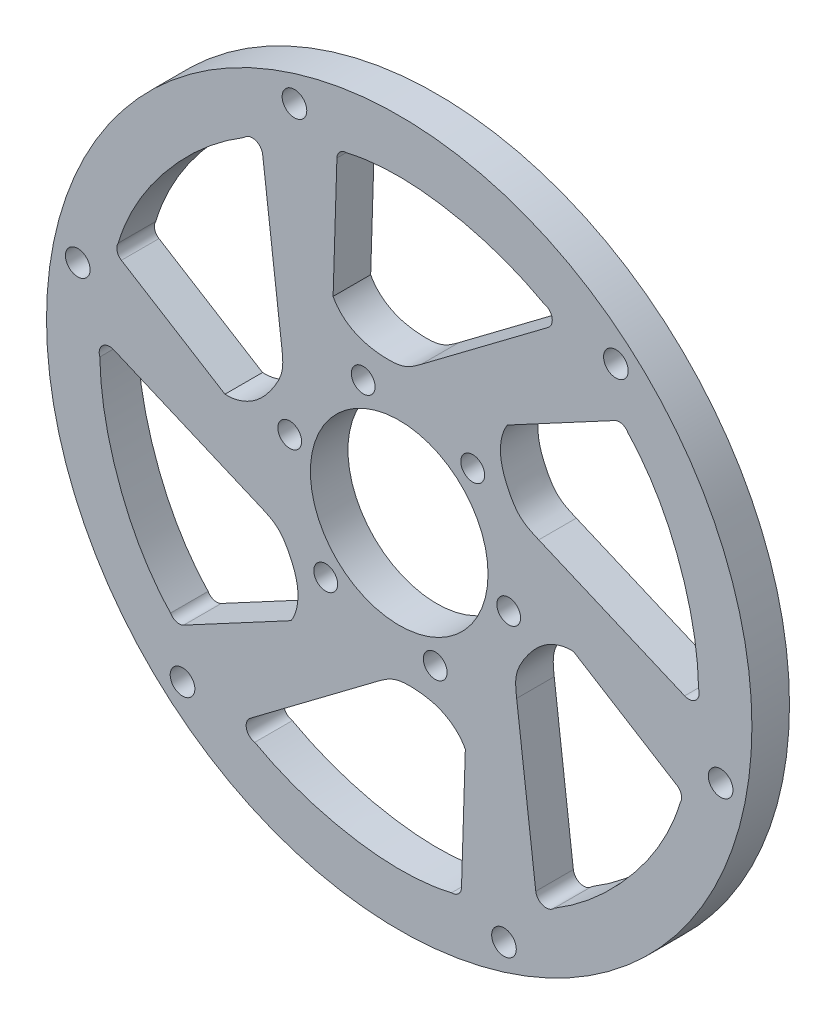
SolidWorks part; units mm, degrees
ref_plane "Piano frontale" through (0, 0, 0) normal (0, 0, 1) x (1, 0, 0)
ref_plane "Piano superiore" through (0, 0, 0) normal (0, 1, 0) x (1, 0, 0)
ref_plane "Piano destro" through (0, 0, 0) normal (1, 0, 0) x (0, 0, -1)
sketch "Schizzo1" plane through (0, 0, 0) normal (0, 0, 1) x (1, 0, 0)
  line L0 (32.5373, 57.7523) -> (32.9478, 70.8459)
  line L1 (42.0185, 56.1733) -> (55.6512, 66.4168)
  line L2 (54.6451, 46.1421) -> (70.3327, 39.4576)
  line L3 (51.2721, 55.1426) -> (62.8167, 61.3339)
  line L4 (52.2712, 30.1915) -> (54.326, 13.2635)
  line L5 (58.3793, 37.6129) -> (69.5134, 30.7107)
  line L6 (37.2706, 24.2722) -> (23.6379, 14.0286)
  line L7 (46.7518, 22.6931) -> (46.3413, 9.5995)
  line L8 (24.644, 34.3033) -> (8.9565, 40.9878)
  line L9 (28.0171, 25.3028) -> (16.4725, 19.1115)
  line L10 (27.018, 50.2539) -> (24.9631, 67.1819)
  line L11 (20.9098, 42.8325) -> (9.7757, 49.7347)
  circle A0 centre (39.6446, 40.2227) radius 37.92
  circle A1 centre (39.6446, 40.2227) radius 35.25 construction
  circle A2 centre (28.3817, 73.625) radius 1.325
  arc A3 (32.9478, 70.8459) -> (34.0242, 71.8569) centre (33.9915, 70.8132) cw
  arc A4 (55.6512, 66.4168) -> (55.1805, 68.4226) centre (54.9753, 67.3163) ccw
  circle A5 centre (39.6446, 40.2227) radius 9.55
  circle A6 centre (39.6446, 40.2227) radius 12 construction
  circle A7 centre (35.7744, 51.5815) radius 1.28
  circle A8 centre (47.5464, 49.2538) radius 1.28
  arc A9 (70.3327, 39.4576) -> (71.8343, 40.8681) centre (70.7737, 40.4927) ccw
  arc A10 (62.8167, 61.3339) -> (64.2304, 60.9072) centre (63.3102, 60.4137) cw
  circle A11 centre (62.9404, 66.6777) radius 1.325
  circle A12 centre (51.4166, 37.895) radius 1.28
  arc A13 (54.326, 13.2635) -> (56.2984, 12.6682) centre (55.4429, 13.3991) ccw
  arc A14 (69.5134, 30.7107) -> (69.8508, 29.273) centre (68.9633, 29.8232) cw
  circle A15 centre (74.2032, 33.2755) radius 1.325
  circle A16 centre (43.5148, 28.8639) radius 1.28
  arc A17 (23.6379, 14.0286) -> (24.1086, 12.0229) centre (24.3138, 13.1291) ccw
  arc A18 (46.3413, 9.5995) -> (45.2649, 8.5885) centre (45.2976, 9.6322) cw
  circle A19 centre (50.9074, 6.8204) radius 1.325
  circle A20 centre (31.7427, 31.1916) radius 1.28
  arc A21 (8.9565, 40.9878) -> (7.4548, 39.5773) centre (8.5154, 39.9527) ccw
  arc A22 (16.4725, 19.1115) -> (15.0587, 19.5382) centre (15.9789, 20.0318) cw
  circle A23 centre (16.3488, 13.7677) radius 1.325
  circle A24 centre (27.8725, 42.5504) radius 1.28
  arc A25 (24.9631, 67.1819) -> (22.9908, 67.7772) centre (23.8462, 67.0464) ccw
  arc A26 (9.7757, 49.7347) -> (9.4384, 51.1724) centre (10.3259, 50.6223) cw
  circle A27 centre (5.0859, 47.17) radius 1.325
  spline S0 degree 3 poles (32.5373, 57.7523) (33.0858, 56.6797) (34.8292, 55.2892) (37.667, 54.792) (40.192, 54.8224) (41.3967, 55.706) (42.0185, 56.1733) knots 0 0 0 0 0.33293 0.577053 0.800008 1 1 1 1
  spline S1 degree 3 poles (34.0242, 71.8569) (37.8131, 72.7545) (45.2372, 72.4651) (52.1771, 70.0854) (55.1805, 68.4226) knots 0 0 0 0 0.531114 1 1 1 1
  spline S2 degree 3 poles (51.2721, 55.1426) (50.6173, 54.1313) (50.2848, 51.9261) (51.2731, 49.22) (52.562, 47.0484) (53.9296, 46.447) (54.6451, 46.1421) knots 0 0 0 0 0.33293 0.577053 0.800008 1 1 1 1
  spline S3 degree 3 poles (64.2304, 60.9072) (66.9022, 58.0747) (70.3636, 51.5005) (71.7727, 44.3005) (71.8343, 40.8681) knots 0 0 0 0 0.531114 1 1 1 1
  spline S4 degree 3 poles (58.3793, 37.6129) (57.1761, 37.6743) (55.1002, 36.8597) (53.2507, 34.6507) (52.0145, 32.4487) (52.1774, 30.9637) (52.2712, 30.1915) knots 0 0 0 0 0.33293 0.577053 0.800008 1 1 1 1
  spline S5 degree 3 poles (69.8508, 29.273) (68.7336, 25.5429) (64.7709, 19.2581) (59.2401, 14.4378) (56.2984, 12.6682) knots 0 0 0 0 0.531114 1 1 1 1
  spline S6 degree 3 poles (46.7518, 22.6931) (46.2034, 23.7658) (44.4599, 25.1563) (41.6222, 25.6535) (39.0971, 25.623) (37.8924, 24.7394) (37.2706, 24.2722) knots 0 0 0 0 0.33293 0.577053 0.800008 1 1 1 1
  spline S7 degree 3 poles (45.2649, 8.5885) (41.476, 7.691) (34.0519, 7.9804) (27.112, 10.36) (24.1086, 12.0229) knots 0 0 0 0 0.531114 1 1 1 1
  spline S8 degree 3 poles (28.0171, 25.3028) (28.6718, 26.3141) (29.0043, 28.5193) (28.016, 31.2254) (26.7271, 33.397) (25.3596, 33.9984) (24.644, 34.3033) knots 0 0 0 0 0.33293 0.577053 0.800008 1 1 1 1
  spline S9 degree 3 poles (15.0587, 19.5382) (12.387, 22.3707) (8.9255, 28.9449) (7.5164, 36.1449) (7.4548, 39.5773) knots 0 0 0 0 0.531114 1 1 1 1
  spline S10 degree 3 poles (20.9098, 42.8325) (22.113, 42.7711) (24.189, 43.5857) (26.0384, 45.7947) (27.2746, 47.9967) (27.1117, 49.4817) (27.018, 50.2539) knots 0 0 0 0 0.33293 0.577053 0.800008 1 1 1 1
  spline S11 degree 3 poles (9.4384, 51.1724) (10.5555, 54.9025) (14.5182, 61.1873) (20.049, 66.0076) (22.9908, 67.7772) knots 0 0 0 0 0.531114 1 1 1 1
  point P122 (39.6446, 40.2227)
  dimension "D1" = 75.84
  dimension "D2" = 70.5
  dimension "D3" = 2.65
  dimension "D4" = 19.1
  dimension "D5" = 24
  dimension "D6" = 2.56
  dimension "D7" = 6
extrude "Estrusione-Estrusione1" add sketch "Schizzo1" along normal blind 4.04
